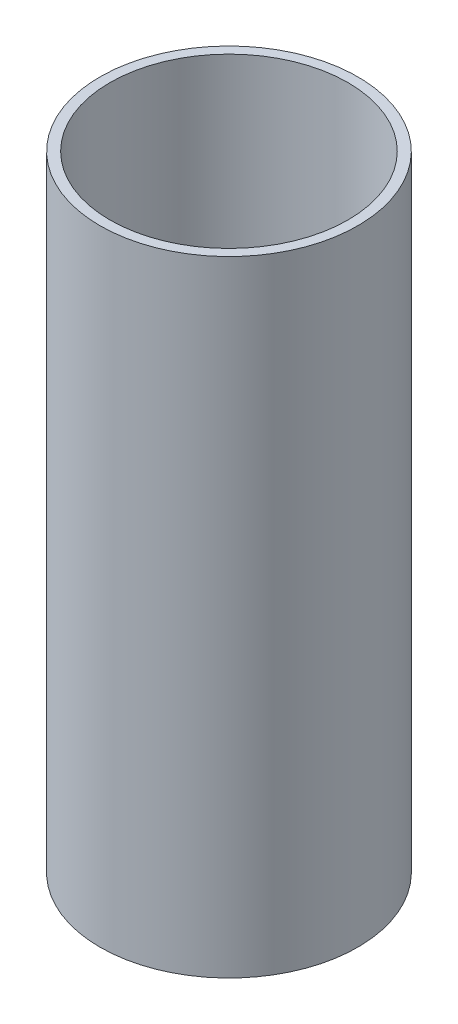
SolidWorks part; units mm, degrees
ref_plane "Front" through (0, 0, 0) normal (0, 0, 1) x (1, 0, 0)
ref_plane "Top" through (0, 0, 0) normal (0, 1, 0) x (1, 0, 0)
ref_plane "Right" through (0, 0, 0) normal (1, 0, 0) x (0, 0, -1)
sketch "Croquis1" plane through (0, 0, 0) normal (0, 1, 0) x (1, 0, 0)
  circle A0 centre (0, 0) radius 38.1
  circle A1 centre (0, 0) radius 41.275
  dimension "D1" = 76.2
  dimension "D2" = 3.175
extrude "Saliente-Extruir1" add sketch "Croquis1" along normal blind 200
